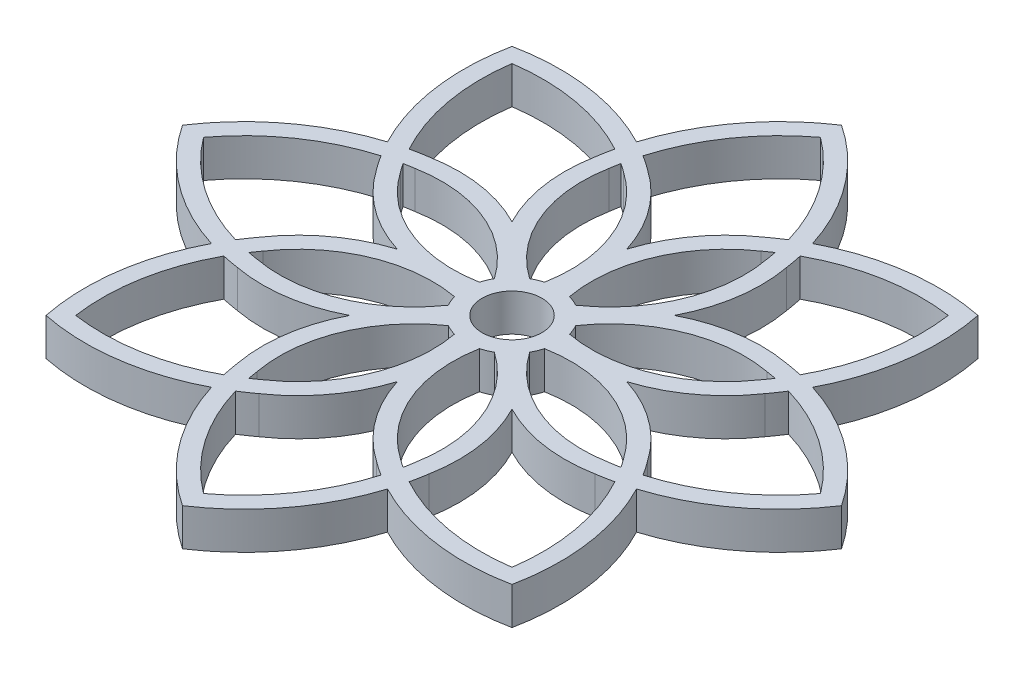
SolidWorks part; units mm, degrees
ref_plane "Front Plane" through (0, 0, 0) normal (0, 0, 1) x (1, 0, 0)
ref_plane "Top Plane" through (0, 0, 0) normal (0, 1, 0) x (1, 0, 0)
ref_plane "Right Plane" through (0, 0, 0) normal (1, 0, 0) x (0, 0, -1)
sketch "Sketch1" plane through (0, 0, 0) normal (0, 1, 0) x (1, 0, 0)
  line L0 (57.456, 142.5165) -> (287.2799, 142.5165) construction
  line L1 (188.9162, 172.8316) -> (188.9162, 346.5474) construction
  line L2 (188.9162, 346.5474) -> (188.9162, -28.2483) construction
  circle A0 centre (188.9162, 172.8316) radius 8
  arc A1 (176.8718, 169.4876) -> (178.0349, 166.6795) centre (188.9162, 172.8316) ccw
  arc A2 (195.0683, 183.7129) -> (209.9965, 219.9065) centre (174.7453, 213.2706) ccw
  arc A3 (209.9965, 219.9065) -> (209.5331, 222.6054) centre (156.5678, 212.1221) ccw
  arc A4 (210.6156, 194.5311) -> (214.5348, 220.663) centre (174.7453, 213.2706) ccw
  arc A5 (214.5348, 220.663) -> (213.6985, 225.1299) centre (156.5678, 212.1221) ccw
  arc A6 (209.9965, 219.9065) -> (189.0375, 255.2607) centre (156.5678, 212.1221) ccw construction
  arc A7 (194.7688, 183.5092) -> (209.9965, 219.9065) centre (174.7453, 213.2706) ccw construction
  arc A8 (214.5348, 220.663) -> (191.8038, 258.936) centre (156.5678, 212.1221) ccw construction
  arc A9 (197.3366, 179.6926) -> (214.5348, 220.663) centre (174.7453, 213.2706) ccw construction
  arc A10 (163.2975, 220.663) -> (164.1338, 225.1299) centre (221.2646, 212.1221) cw
  arc A11 (167.2167, 194.5311) -> (163.2975, 220.663) centre (203.087, 213.2706) cw
  arc A12 (167.8358, 219.9065) -> (168.2992, 222.6054) centre (221.2646, 212.1221) cw
  arc A13 (182.7641, 183.7129) -> (167.8358, 219.9065) centre (203.087, 213.2706) cw
  arc A14 (188.9162, 203.5193) -> (204.623, 224.7686) centre (227.5311, 191.406) cw
  arc A15 (192.2602, 184.876) -> (207.2971, 221.0247) centre (227.5311, 191.406) cw
  arc A16 (204.623, 224.7686) -> (208.3729, 227.3358) centre (239.5725, 177.7404) cw
  arc A17 (207.2971, 221.0247) -> (209.5331, 222.6054) centre (239.5725, 177.7404) cw
  arc A18 (237.1092, 191.2126) -> (238.6899, 193.4486) centre (193.8249, 223.488) ccw
  arc A19 (240.8532, 188.5385) -> (243.4204, 192.2883) centre (193.8249, 223.488) ccw
  arc A20 (200.9606, 176.1757) -> (237.1092, 191.2126) centre (207.4905, 211.4466) ccw
  arc A21 (219.6038, 172.8316) -> (240.8532, 188.5385) centre (207.4905, 211.4466) ccw
  arc A22 (210.6156, 194.5311) -> (236.7476, 198.4502) centre (229.3551, 158.6608) cw
  arc A23 (199.7974, 178.9837) -> (235.9911, 193.912) centre (229.3551, 158.6608) cw
  arc A24 (236.7476, 198.4502) -> (241.2144, 197.614) centre (228.2066, 140.4832) cw
  arc A25 (235.9911, 193.912) -> (238.6899, 193.4486) centre (228.2066, 140.4832) cw
  arc A26 (235.9911, 151.7513) -> (238.6899, 152.2147) centre (228.2066, 205.18) ccw
  arc A27 (236.7476, 147.213) -> (241.2144, 148.0493) centre (228.2066, 205.18) ccw
  arc A28 (199.7974, 166.6795) -> (235.9911, 151.7513) centre (229.3551, 187.0025) ccw
  arc A29 (210.6156, 151.1322) -> (236.7476, 147.213) centre (229.3551, 187.0025) ccw
  arc A30 (219.6038, 172.8316) -> (240.8532, 157.1248) centre (207.4905, 134.2167) cw
  arc A31 (200.9606, 169.4876) -> (237.1092, 154.4507) centre (207.4905, 134.2167) cw
  arc A32 (240.8532, 157.1248) -> (243.4204, 153.3749) centre (193.8249, 122.1753) cw
  arc A33 (237.1092, 154.4507) -> (238.6899, 152.2147) centre (193.8249, 122.1753) cw
  arc A34 (207.2971, 124.6386) -> (209.5331, 123.0579) centre (239.5725, 167.9229) ccw
  arc A35 (204.623, 120.8946) -> (208.3729, 118.3274) centre (239.5725, 167.9229) ccw
  arc A36 (192.2602, 160.7872) -> (207.2971, 124.6386) centre (227.5311, 154.2572) ccw
  arc A37 (188.9162, 142.144) -> (204.623, 120.8946) centre (227.5311, 154.2572) ccw
  arc A38 (210.6156, 151.1322) -> (214.5348, 125.0002) centre (174.7453, 132.3927) cw
  arc A39 (195.0683, 161.9504) -> (209.9965, 125.7567) centre (174.7453, 132.3927) cw
  arc A40 (214.5348, 125.0002) -> (213.6985, 120.5334) centre (156.5678, 133.5412) cw
  arc A41 (209.9965, 125.7567) -> (209.5331, 123.0579) centre (156.5678, 133.5412) cw
  arc A42 (167.8358, 125.7567) -> (168.2992, 123.0579) centre (221.2646, 133.5412) ccw
  arc A43 (163.2975, 125.0002) -> (164.1338, 120.5334) centre (221.2646, 133.5412) ccw
  arc A44 (182.7641, 161.9504) -> (167.8358, 125.7567) centre (203.087, 132.3927) ccw
  arc A45 (167.2167, 151.1322) -> (163.2975, 125.0002) centre (203.087, 132.3927) ccw
  arc A46 (188.9162, 142.144) -> (173.2093, 120.8946) centre (150.3012, 154.2572) cw
  arc A47 (185.5721, 160.7872) -> (170.5352, 124.6386) centre (150.3012, 154.2572) cw
  arc A48 (173.2093, 120.8946) -> (169.4594, 118.3274) centre (138.2598, 167.9229) cw
  arc A49 (170.5352, 124.6386) -> (168.2992, 123.0579) centre (138.2598, 167.9229) cw
  arc A50 (140.7231, 154.4507) -> (139.1424, 152.2147) centre (184.0074, 122.1753) ccw
  arc A51 (136.9792, 157.1248) -> (134.412, 153.3749) centre (184.0074, 122.1753) ccw
  arc A52 (176.8718, 169.4876) -> (140.7231, 154.4507) centre (170.3418, 134.2167) ccw
  arc A53 (158.2285, 172.8316) -> (136.9792, 157.1248) centre (170.3418, 134.2167) ccw
  arc A54 (167.2167, 151.1322) -> (141.0848, 147.213) centre (148.4772, 187.0025) cw
  arc A55 (178.0349, 166.6795) -> (141.8412, 151.7513) centre (148.4772, 187.0025) cw
  arc A56 (141.0848, 147.213) -> (136.6179, 148.0493) centre (149.6257, 205.18) cw
  arc A57 (141.8412, 151.7513) -> (139.1424, 152.2147) centre (149.6257, 205.18) cw
  arc A58 (141.8412, 193.912) -> (139.1424, 193.4486) centre (149.6257, 140.4832) ccw
  arc A59 (141.0848, 198.4502) -> (136.6179, 197.614) centre (149.6257, 140.4832) ccw
  arc A60 (178.0349, 178.9837) -> (141.8412, 193.912) centre (148.4772, 158.6608) ccw
  arc A61 (167.2167, 194.5311) -> (141.0848, 198.4502) centre (148.4772, 158.6608) ccw
  arc A62 (158.2285, 172.8316) -> (136.9792, 188.5385) centre (170.3418, 211.4466) cw
  arc A63 (176.8718, 176.1757) -> (140.7231, 191.2126) centre (170.3418, 211.4466) cw
  arc A64 (136.9792, 188.5385) -> (134.412, 192.2883) centre (184.0074, 223.488) cw
  arc A65 (140.7231, 191.2126) -> (139.1424, 193.4486) centre (184.0074, 223.488) cw
  arc A66 (170.5352, 221.0247) -> (168.2992, 222.6054) centre (138.2598, 177.7404) ccw
  arc A67 (173.2093, 224.7686) -> (169.4594, 227.3358) centre (138.2598, 177.7404) ccw
  arc A68 (185.5721, 184.876) -> (170.5352, 221.0247) centre (150.3012, 191.406) ccw
  arc A69 (188.9162, 203.5193) -> (173.2093, 224.7686) centre (150.3012, 191.406) ccw
  arc A70 (132.0616, 196.3816) -> (100.7718, 172.8316) centre (149.6257, 140.4832) ccw
  arc A71 (132.0616, 196.3816) -> (126.5887, 235.1591) centre (184.0074, 223.488) cw
  arc A72 (134.412, 192.2883) -> (106.396, 172.8316) centre (149.6257, 140.4832) ccw
  arc A73 (136.6179, 197.614) -> (130.5656, 231.1822) centre (184.0074, 223.488) cw
  arc A74 (178.0349, 178.9837) -> (176.8718, 176.1757) centre (188.9162, 172.8316) ccw
  circle A75 centre (188.9162, 172.8316) radius 12.5 construction
  arc A76 (164.1338, 225.1299) -> (130.5656, 231.1822) centre (138.2598, 177.7404) ccw
  arc A77 (165.3662, 229.6862) -> (126.5887, 235.1591) centre (138.2598, 177.7404) ccw
  arc A78 (165.3662, 229.6862) -> (188.9162, 260.976) centre (221.2646, 212.1221) cw
  arc A79 (169.4594, 227.3358) -> (188.9162, 255.3518) centre (221.2646, 212.1221) cw
  arc A80 (185.5721, 184.876) -> (182.7641, 183.7129) centre (188.9162, 172.8316) ccw
  arc A81 (195.0683, 183.7129) -> (192.2602, 184.876) centre (188.9162, 172.8316) ccw
  arc A82 (200.9606, 176.1757) -> (199.7974, 178.9837) centre (188.9162, 172.8316) ccw
  arc A83 (199.7974, 166.6795) -> (200.9606, 169.4876) centre (188.9162, 172.8316) ccw
  arc A84 (192.2602, 160.7872) -> (195.0683, 161.9504) centre (188.9162, 172.8316) ccw
  arc A85 (182.7641, 161.9504) -> (185.5721, 160.7872) centre (188.9162, 172.8316) ccw
  arc A86 (169.4594, 118.3274) -> (188.9162, 90.3115) centre (221.2646, 133.5412) ccw
  arc A87 (164.1338, 120.5334) -> (130.5656, 114.4811) centre (138.2598, 167.9229) cw
  arc A88 (165.3662, 115.9771) -> (188.9162, 84.6873) centre (221.2646, 133.5412) ccw
  arc A89 (208.3729, 118.3274) -> (188.9162, 90.3115) centre (156.5678, 133.5412) cw
  arc A90 (212.4661, 115.9771) -> (251.2436, 110.5042) centre (239.5725, 167.9229) ccw
  arc A91 (213.6985, 120.5334) -> (247.2667, 114.4811) centre (239.5725, 167.9229) ccw
  arc A92 (245.7707, 149.2817) -> (277.0605, 172.8316) centre (228.2066, 205.18) ccw
  arc A93 (243.4204, 153.3749) -> (271.4363, 172.8316) centre (228.2066, 205.18) ccw
  arc A94 (241.2144, 148.0493) -> (247.2667, 114.4811) centre (193.8249, 122.1753) cw
  arc A95 (243.4204, 192.2883) -> (271.4363, 172.8316) centre (228.2066, 140.4832) cw
  arc A96 (241.2144, 197.614) -> (247.2667, 231.1822) centre (193.8249, 223.488) ccw
  arc A97 (245.7707, 196.3816) -> (277.0605, 172.8316) centre (228.2066, 140.4832) cw
  arc A98 (245.7707, 196.3816) -> (251.2436, 235.1591) centre (193.8249, 223.488) ccw
  arc A99 (213.6985, 225.1299) -> (247.2667, 231.1822) centre (239.5725, 177.7404) cw
  arc A100 (208.3729, 227.3358) -> (188.9162, 255.3518) centre (156.5678, 212.1221) ccw
  arc A101 (212.4661, 229.6862) -> (188.9162, 260.976) centre (156.5678, 212.1221) ccw
  arc A102 (212.4661, 229.6862) -> (251.2436, 235.1591) centre (239.5725, 177.7404) cw
  arc A103 (132.0616, 149.2817) -> (100.7718, 172.8316) centre (149.6257, 205.18) cw
  arc A104 (134.412, 153.3749) -> (106.396, 172.8316) centre (149.6257, 205.18) cw
  arc A105 (136.6179, 148.0493) -> (130.5656, 114.4811) centre (184.0074, 122.1753) ccw
  arc A106 (132.0616, 149.2817) -> (126.5887, 110.5042) centre (184.0074, 122.1753) ccw
  arc A107 (212.4661, 115.9771) -> (188.9162, 84.6873) centre (156.5678, 133.5412) cw
  arc A108 (245.7707, 149.2817) -> (251.2436, 110.5042) centre (193.8249, 122.1753) cw
  arc A109 (165.3662, 115.9771) -> (126.5887, 110.5042) centre (138.2598, 167.9229) cw
  point P102 (200.87, 176.4863)
  point P142 (188.9162, 172.8316)
  dimension "D1" = 16
  dimension "D2" = 4.5
  dimension "D3" = 4.6
  dimension "D4" = 8
extrude "Boss-Extrude1" add sketch "Sketch1" along normal blind 10
